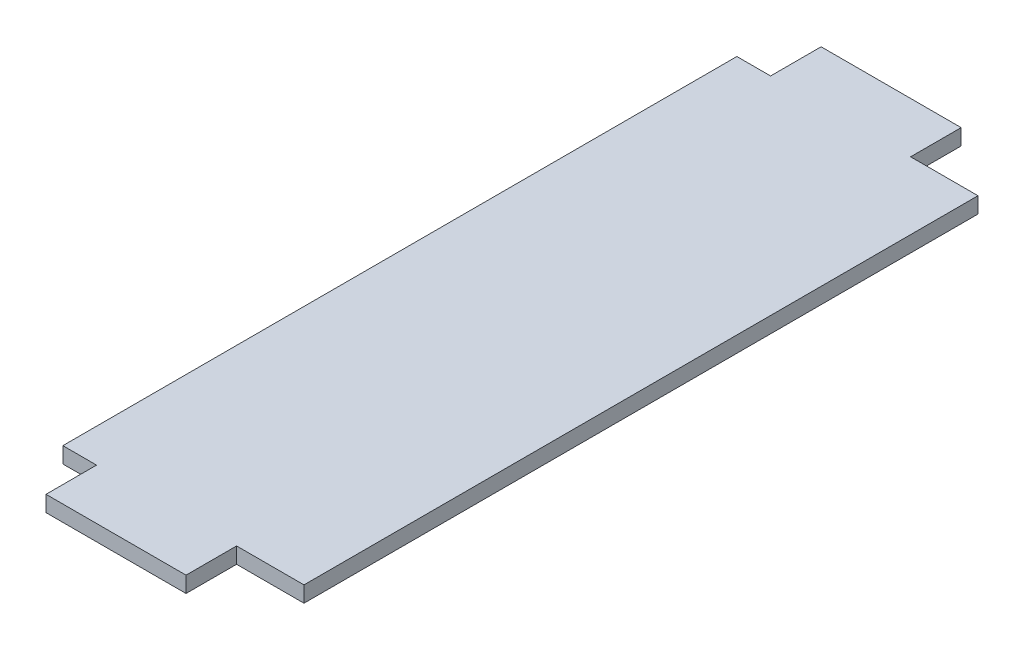
SolidWorks part; units mm, degrees
ref_plane "Front Plane" through (0, 0, 0) normal (0, 0, 1) x (1, 0, 0)
ref_plane "Top Plane" through (0, 0, 0) normal (0, 1, 0) x (1, 0, 0)
ref_plane "Right Plane" through (0, 0, 0) normal (1, 0, 0) x (0, 0, -1)
sketch "Sketch1" plane through (0, 0, 0) normal (0, 1, 0) x (1, 0, 0)
  line L0 (-22.7168, 66.4972) -> (22.7168, 66.4972) construction
  line L1 (22.7168, -73.025) -> (-22.7168, -73.025)
  line L2 (22.7168, -73.025) -> (22.7168, 73.025)
  line L3 (22.7168, 73.025) -> (-22.7168, 73.025)
  line L4 (-22.7168, -73.025) -> (-22.7168, 73.025)
  line L5 (22.7168, -73.025) -> (-22.7168, 73.025) construction
  line L6 (22.7168, 73.025) -> (-22.7168, -73.025) construction
  line L7 (-22.7168, -66.4972) -> (22.7168, -66.4972) construction
  line L8 (-22.7168, 66.4972) -> (-22.7168, -66.4972) construction
  line L9 (22.7168, 66.4972) -> (22.7168, -66.4972) construction
  line L20 (-22.7168, -73.025) -> (-16.3668, -73.025)
  line L21 (-22.7168, -73.025) -> (-22.7168, -63.5)
  line L22 (-22.7168, -63.5) -> (-16.3668, -63.5)
  line L23 (-16.3668, -73.025) -> (-16.3668, -63.5)
  line L24 (22.7168, -73.025) -> (10.0168, -73.025)
  line L25 (22.7168, -73.025) -> (22.7168, -63.5)
  line L26 (22.7168, -63.5) -> (10.0168, -63.5)
  line L27 (10.0168, -73.025) -> (10.0168, -63.5)
  line L28 (-22.7168, 73.025) -> (-16.3668, 73.025)
  line L29 (-22.7168, 73.025) -> (-22.7168, 63.5)
  line L30 (-22.7168, 63.5) -> (-16.3668, 63.5)
  line L31 (-16.3668, 73.025) -> (-16.3668, 63.5)
  line L32 (22.7168, 73.025) -> (10.0168, 73.025)
  line L33 (22.7168, 73.025) -> (22.7168, 63.5)
  line L34 (22.7168, 63.5) -> (10.0168, 63.5)
  line L35 (10.0168, 73.025) -> (10.0168, 63.5)
  point P0 (0, 0)
  point P10 (22.7168, 0)
  point P11 (22.7168, 0)
  dimension "D1" = 45.4337
  dimension "D2" = 146.05
  dimension "D3" = 132.9944
  dimension "D4" = 6.35
  dimension "D5" = 12.7
  dimension "D6" = 127
extrude "Boss-Extrude1" add sketch "Sketch1" along normal blind 2.9972
